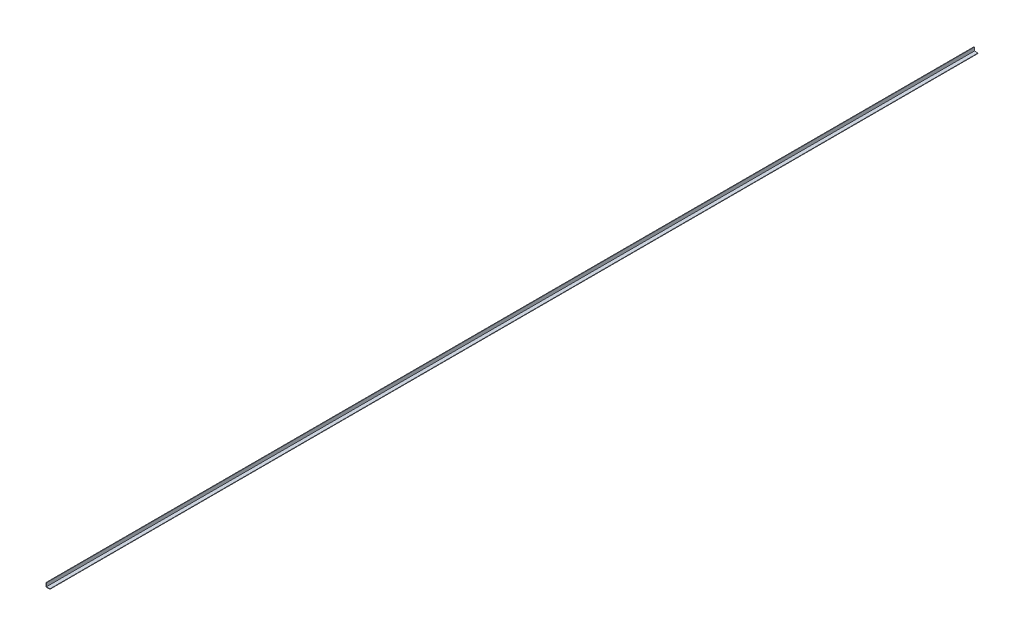
SolidWorks part; units mm, degrees
material "ASTM A36 Acero"
ref_plane "Alzado" through (0, 0, 0) normal (0, 0, 1) x (1, 0, 0)
ref_plane "Planta" through (0, 0, 0) normal (0, 1, 0) x (1, 0, 0)
ref_plane "Vista lateral" through (0, 0, 0) normal (1, 0, 0) x (0, 0, -1)
sketch "Croquis1" plane through (0, 0, 0) normal (0, 0, 1) x (1, 0, 0)
  line L0 (0, 25.8) -> (0, 0)
  line L1 (0, 0) -> (25.8, 0)
  line L2 (25.8, 0) -> (25.8, 2.7)
  line L3 (25.8, 2.7) -> (2.7, 2.7)
  line L4 (2.7, 2.7) -> (2.7, 25.8)
  line L5 (2.7, 25.8) -> (0, 25.8)
  dimension "D1" = 2.7
  dimension "D2" = 25.8
extrude "Saliente-Extruir1" add sketch "Croquis1" against normal blind 6100
